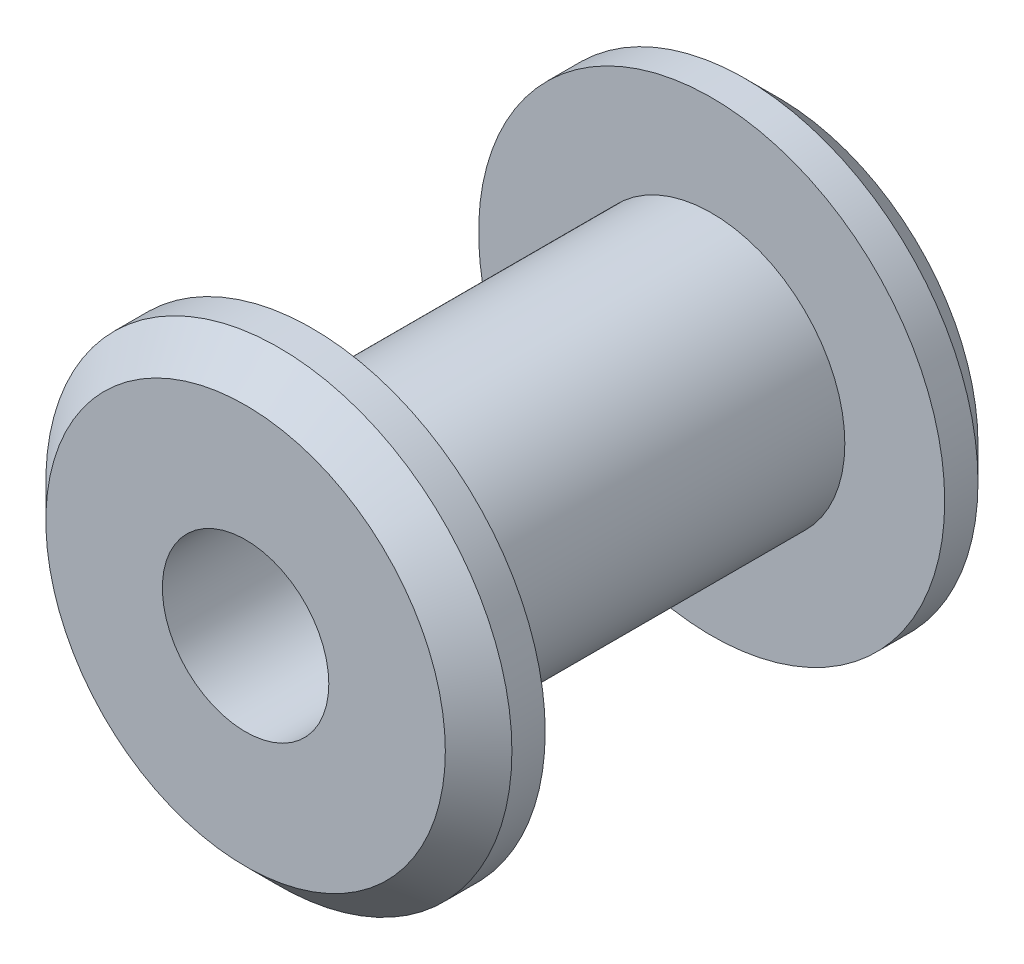
SolidWorks part; units mm, degrees
ref_plane "Front (XY)" through (0, 0, 0) normal (0, 0, 1) x (1, 0, 0)
ref_plane "Top (XZ)" through (0, 0, 0) normal (0, 1, 0) x (1, 0, 0)
ref_plane "Right (YZ)" through (0, 0, 0) normal (1, 0, 0) x (0, 0, -1)
sketch "Sketch1" plane through (0, 0, 0) normal (0, 0, 1) x (1, 0, 0)
  circle A0 centre (0, 0) radius 4
  dimension "D1" = 8
extrude "Boss-Extrude1" add sketch "Sketch1" along normal mid plane 12
sketch "Sketch2" plane through (0, 0, 6) normal (0, 0, 1) x (1, 0, 0)
  circle A2 centre (0, 0) radius 7
  circle A3 centre (0, 0) radius 7
  dimension "D1" = 3
extrude "Boss-Extrude2" add sketch "Sketch2" along normal blind 2
pattern_linear "LPattern1" count 2 spacing 14 along (0, 0, -1) of "Boss-Extrude2"
sketch "Sketch3" plane through (0, 0, 0) normal (0, 0, 1) x (1, 0, 0)
  circle A0 centre (0, 0) radius 2.5
  dimension "D1" = 5
extrude "Cut-Extrude1" cut sketch "Sketch3" against normal through all both and the other way through all
chamfer "Chamfer1" distance 1 angle 45 2 edges at (7, 0, -8) (7, 0, 8)
